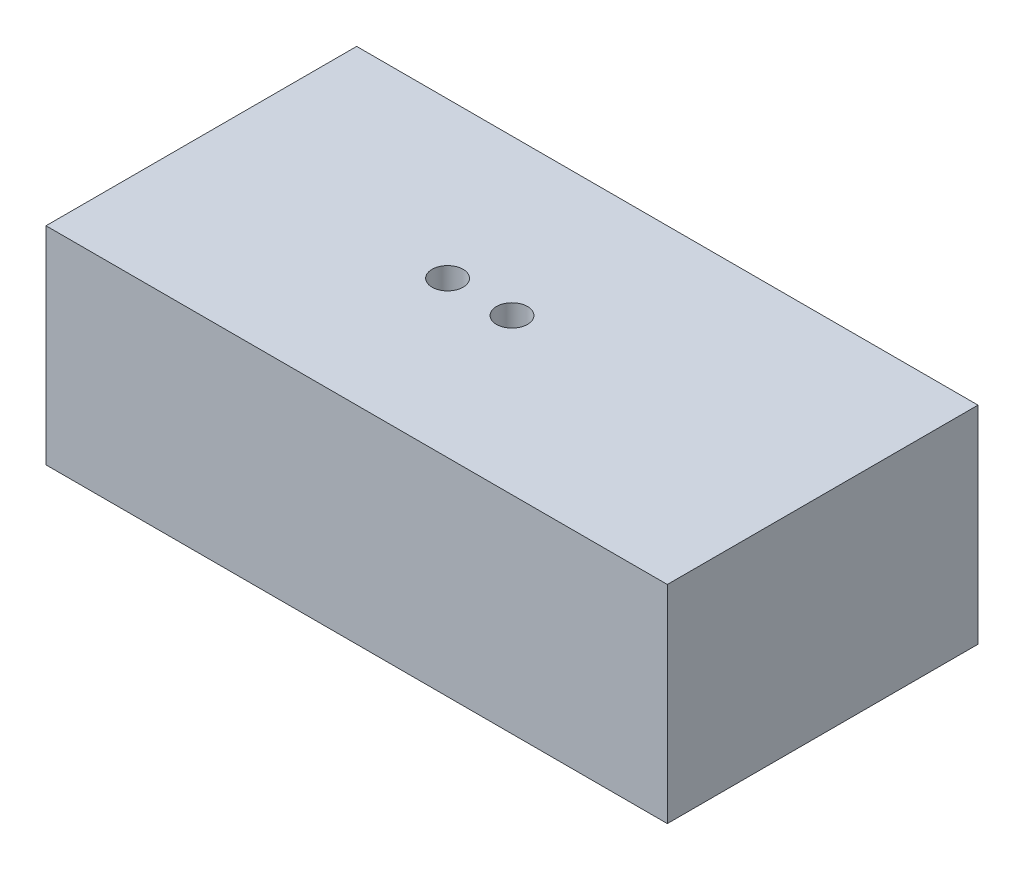
SolidWorks part; units mm, degrees
ref_plane "Front Plane" through (0, 0, 0) normal (0, 0, 1) x (1, 0, 0)
ref_plane "Top Plane" through (0, 0, 0) normal (0, 1, 0) x (1, 0, 0)
ref_plane "Right Plane" through (0, 0, 0) normal (1, 0, 0) x (0, 0, -1)
sketch "Sketch1" plane through (0, 0, 0) normal (0, 1, 0) x (1, 0, 0)
  line L0 (4.8547, 0) -> (-10.1453, 0) construction
  line L1 (-15, -7.5) -> (15, -7.5)
  line L2 (-15, -7.5) -> (-15, 7.5)
  line L3 (-15, 7.5) -> (15, 7.5)
  line L4 (15, -7.5) -> (15, 7.5)
  line L5 (0, 0) -> (0, 7.5) construction
  circle A0 centre (0, 0) radius 0.75
  circle A1 centre (-3.11, 0) radius 0.75
  dimension "D3" = 1.5
  dimension "D4" = 3.11
  dimension "D6" = 1.5
  dimension "D1" = 30
  dimension "D2" = 15
extrude "Boss-Extrude1" add sketch "Sketch1" along normal blind 10
